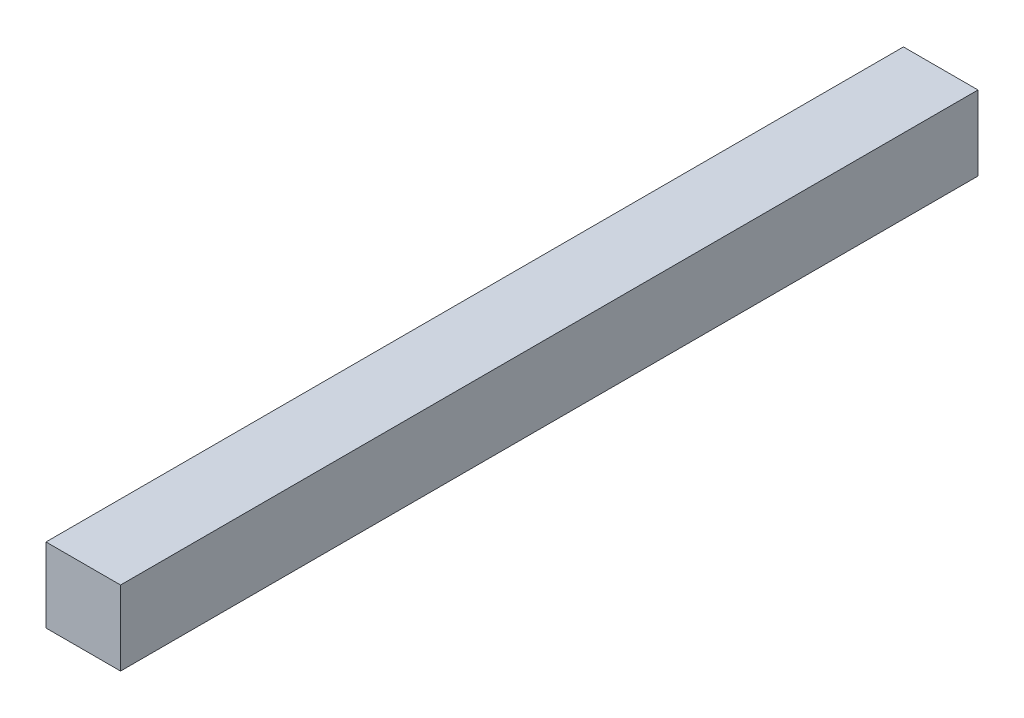
SolidWorks part; units mm, degrees
ref_plane "Front Plane" through (0, 0, 0) normal (0, 0, 1) x (1, 0, 0)
ref_plane "Top Plane" through (0, 0, 0) normal (0, 1, 0) x (1, 0, 0)
ref_plane "Right Plane" through (0, 0, 0) normal (1, 0, 0) x (0, 0, -1)
sketch "Sketch1" plane through (0, 0, 0) normal (0, 0, 1) x (1, 0, 0)
  line L1 (0, 0) -> (20, 0)
  line L2 (0, 0) -> (0, -20)
  line L3 (0, -20) -> (20, -20)
  line L4 (20, 0) -> (20, -20)
  dimension "D1" = 20
extrude "Boss-Extrude1" add sketch "Sketch1" along normal blind 230
